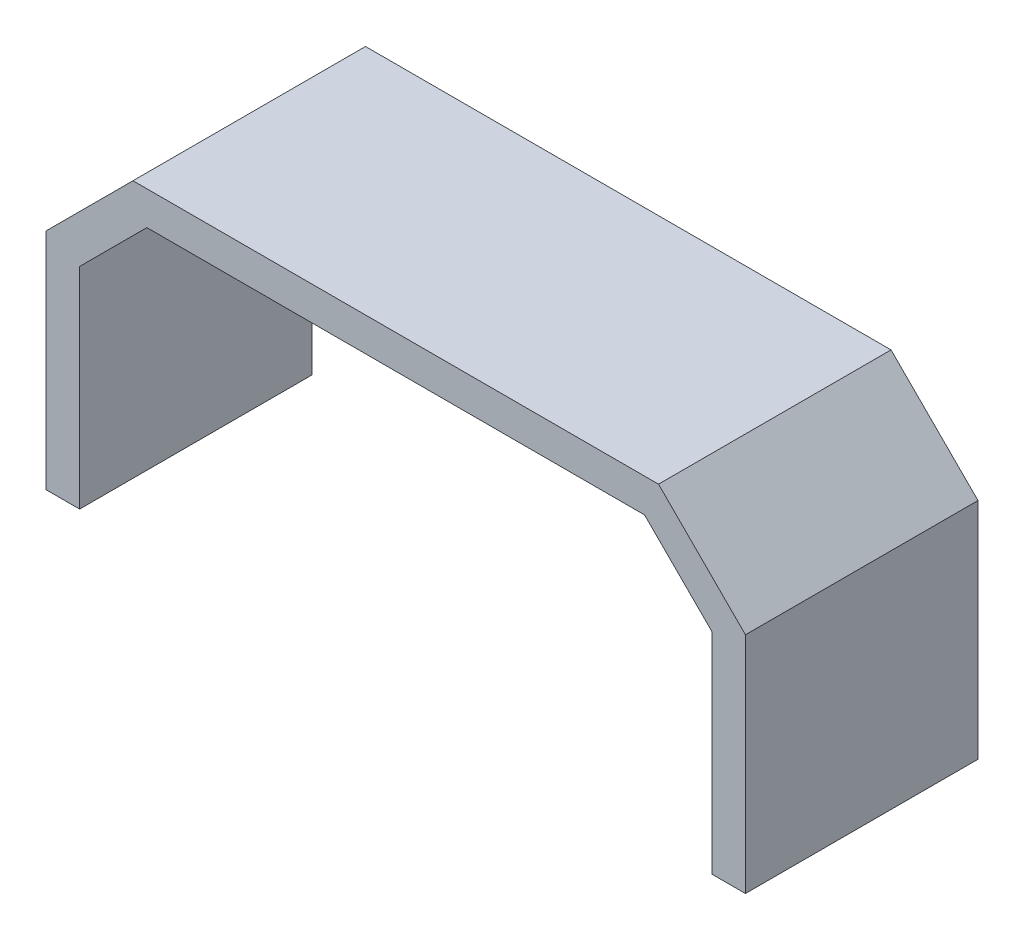
SolidWorks part; units mm, degrees
ref_plane "Спереди" through (0, 0, 0) normal (0, 0, 1) x (1, 0, 0)
ref_plane "Сверху" through (0, 0, 0) normal (0, 1, 0) x (1, 0, 0)
ref_plane "Справа" through (0, 0, 0) normal (1, 0, 0) x (0, 0, -1)
sketch "Эскиз1" plane through (0, 0, 0) normal (0, 0, 1) x (1, 0, 0)
  line L0 (-47, 0) -> (-47, 31.2489)
  line L1 (-47, 31.2489) -> (-37, 41.2489)
  line L2 (-37, 41.2489) -> (37, 41.2489)
  line L3 (37, 41.2489) -> (47, 31.2489)
  line L4 (47, 31.2489) -> (47, 0)
  line L5 (0, 0) -> (0, 41.2489) construction
  line L6 (-47, 31.2489) -> (47, 31.2489) construction
  line L7 (-52, 0) -> (-52, 33.32)
  line L8 (-52, 33.32) -> (-39.0711, 46.2489)
  line L9 (-39.0711, 46.2489) -> (39.0711, 46.2489)
  line L10 (39.0711, 46.2489) -> (52, 33.32)
  line L11 (52, 33.32) -> (52, 0)
  line L12 (-52, 0) -> (-47, 0)
  line L13 (47, 0) -> (52, 0)
  dimension "D1" = 94
  dimension "D2" = 45
  dimension "D4" = 33.32
  dimension "D5" = 10
  dimension "D3" = 5
extrude "Бобышка-Вытянуть1" add sketch "Эскиз1" along normal blind 34.575
mirror "Зеркальное отражение1" [suppressed]
